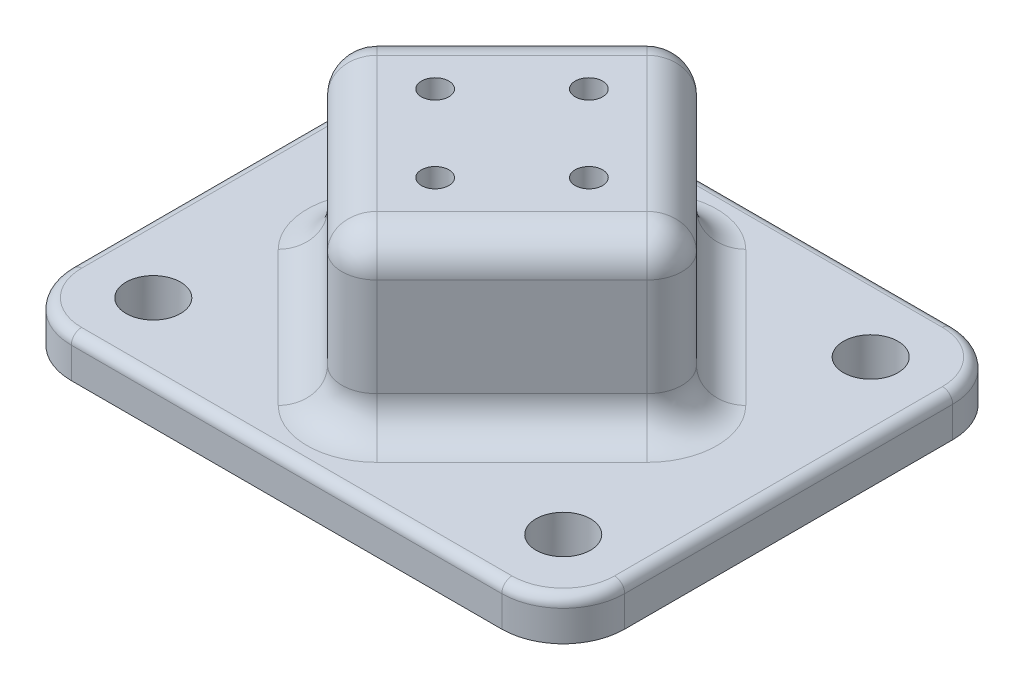
SolidWorks part; units mm, degrees
ref_plane "Front Plane" through (0, 0, 0) normal (0, 0, 1) x (1, 0, 0)
ref_plane "Top Plane" through (0, 0, 0) normal (0, 1, 0) x (1, 0, 0)
ref_plane "Right Plane" through (0, 0, 0) normal (1, 0, 0) x (0, 0, -1)
sketch "Sketch4" plane through (0, 0, 0) normal (0, 1, 0) x (1, 0, 0)
  line L1 (-31.75, -25.4) -> (31.75, -25.4)
  line L2 (-31.75, -25.4) -> (-31.75, 25.4)
  line L3 (-31.75, 25.4) -> (31.75, 25.4)
  line L4 (31.75, -25.4) -> (31.75, 25.4)
  line L5 (-31.75, -25.4) -> (31.75, 25.4) construction
  line L6 (-31.75, 25.4) -> (31.75, -25.4) construction
  point P0 (0, 0)
  dimension "D1" = 63.5
  dimension "D2" = 50.8
extrude "Boss-Extrude2" add sketch "Sketch4" along normal blind 5.08
sketch "Sketch5" plane through (0, 5.08, 0) normal (0, 1, 0) x (1, 0, 0)
  line L0 (31.75, 25.4) -> (-31.75, 25.4) construction
  line L1 (31.75, -25.4) -> (31.75, 25.4) construction
  point P0 (-25.4, 19.05)
  point P1 (25.4, 19.05)
  point P2 (25.4, -19.05)
  point P3 (-25.4, -19.05)
  dimension "D1" = 38.1
  dimension "D2" = 50.8
  dimension "D3" = 38.1
  dimension "D4" = 50.8
  dimension "D5" = 6.35
  dimension "D6" = 6.35
hole_wizard "1/4 Clearance Hole2" positions "3DSketch2" profile "Sketch6" hole size "1/4" standard "ANSI Inch" end condition up to next
sketch3d "3DSketch2"
  point P0 (-25.4, 5.08, -19.05)
  point P3 (25.4, 5.08, -19.05)
  point P6 (25.4, 5.08, 19.05)
  point P9 (-25.4, 5.08, 19.05)
sketch "Sketch6" plane through (-25.4, 5.08, -19.05) normal (1, 0, 0) x (0, 0, 1)
  line L0 (0, 0) -> (0, 5.08)
  line L1 (0, 5.08) -> (3.3782, 5.08)
  line L2 (3.3782, 5.08) -> (3.3782, 0)
  line L5 (3.3782, 0) -> (0, 0)
  line L11 (0, -6.35) -> (0, 107.95) construction
  dimension "Thru Hole Dia." = 6.7564
  dimension "Thru Hole Depth" = 5.08
sketch "Sketch7" plane through (0, 5.08, 0) normal (0, 1, 0) x (1, 0, 0)
  line L0 (0, 22.86) -> (22.86, 0)
  line L1 (22.86, 0) -> (0, -22.86)
  line L2 (0, -22.86) -> (-22.86, 0)
  line L3 (-22.86, 0) -> (0, 22.86)
  line L4 (31.75, 25.4) -> (-31.75, 25.4) construction
  line L5 (-31.75, -25.4) -> (31.75, -25.4) construction
  dimension "D1" = 2.54
  dimension "D2" = 2.54
  dimension "D3" = 32.3289
extrude "Boss-Extrude3" add sketch "Sketch7" along normal blind 20.828
sketch "Sketch8" plane through (0, 25.908, 0) normal (0, 1, 0) x (1, 0, 0)
  point P0 (0, 9.525)
  point P1 (9.525, 0)
  point P2 (0, -9.525)
  point P3 (-9.525, 0)
  dimension "D1" = 9.525
  dimension "D2" = 9.525
  dimension "D3" = 9.525
  dimension "D4" = 9.525
hole_wizard "M3 Clearance Hole1" positions "3DSketch3" profile "Sketch9" hole size "M3" standard "ANSI Metric" end condition up to next
sketch3d "3DSketch3"
  point P0 (0, 25.908, -9.525)
  point P3 (9.525, 25.908, 0)
  point P6 (0, 25.908, 9.525)
  point P9 (-9.525, 25.908, 0)
sketch "Sketch9" plane through (0, 25.908, -9.525) normal (1, 0, 0) x (0, 0, 1)
  line L0 (0, 0) -> (0, 25.908)
  line L1 (0, 25.908) -> (1.7, 25.908)
  line L2 (1.7, 25.908) -> (1.7, 0)
  line L5 (1.7, 0) -> (0, 0)
  line L11 (0, -6.35) -> (0, 107.95) construction
  dimension "Thru Hole Dia." = 3.4
  dimension "Thru Hole Depth" = 25.908
sketch "Sketch12" plane through (0, 0, 0) normal (0, -1, 0) x (-1, 0, 0)
  line L0 (0, -19.05) -> (-19.05, 0)
  line L1 (-19.05, 0) -> (0, 19.05)
  line L2 (0, 19.05) -> (19.05, 0)
  line L3 (19.05, 0) -> (0, -19.05)
  line L4 (31.75, -25.4) -> (-31.75, -25.4) construction
  dimension "D1" = 90
  dimension "D2" = 6.35
extrude "Cut-Extrude1" cut sketch "Sketch12" against normal blind 20.828
fillet "Fillet2" radius 4.318 12 edges at (-11.43, 25.908, -11.43) (-11.43, 25.908, 11.43) (11.43, 25.908, 11.43) (11.43, 25.908, -11.43) (11.43, 5.08, -11.43) (11.43, 5.08, 11.43) (-11.43, 5.08, 11.43) (-11.43, 5.08, -11.43) (-22.86, 15.494, 0) (0, 15.494, -22.86) (22.86, 15.494, 0) (0, 15.494, 22.86)
sketch "Sketch13" plane through (0, 0, 0) normal (0, -1, 0) x (1, 0, 0)
  line L0 (-31.75, 25.4) -> (31.75, 25.4)
  line L1 (31.75, 25.4) -> (31.75, -25.4)
  line L2 (31.75, -25.4) -> (-31.75, -25.4)
  line L3 (-31.75, -25.4) -> (-31.75, 25.4)
  line L4 (-34.29, 27.94) -> (34.29, 27.94)
  line L5 (34.29, 27.94) -> (34.29, -27.94)
  line L6 (34.29, -27.94) -> (-34.29, -27.94)
  line L7 (-34.29, -27.94) -> (-34.29, 27.94)
  dimension "D1" = 2.54
  dimension "D2" = 2.54
  dimension "D3" = 2.54
  dimension "D4" = 2.54
extrude "Boss-Extrude4" add sketch "Sketch13" against normal blind 5.08
fillet "Fillet3" radius 7.62 4 edges at (-34.29, 2.54, 27.94) (-34.29, 2.54, -27.94) (34.29, 2.54, 27.94) (34.29, 2.54, -27.94)
fillet "Fillet4" radius 1.27 8 edges at (-32.0582, 5.08, -25.7082) (-34.29, 5.08, 0) (-32.0582, 5.08, 25.7082) (0, 5.08, 27.94) (32.0582, 5.08, 25.7082) (34.29, 5.08, 0) (32.0582, 5.08, -25.7082) (0, 5.08, -27.94)
